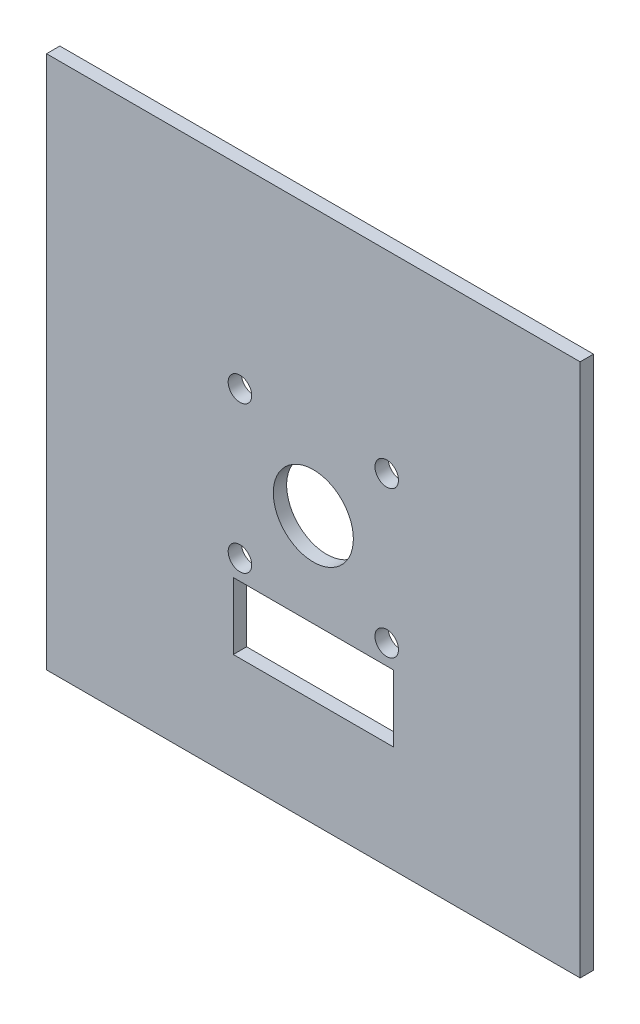
SolidWorks part; units mm, degrees
ref_plane "Front Plane" through (0, 0, 0) normal (0, 0, 1) x (1, 0, 0)
ref_plane "Top Plane" through (0, 0, 0) normal (0, 1, 0) x (1, 0, 0)
ref_plane "Right Plane" through (0, 0, 0) normal (1, 0, 0) x (0, 0, -1)
sketch "Sketch1" plane through (0, 0, 0) normal (0, 0, 1) x (1, 0, 0)
  line L0 (-259.5239, 0) -> (259.5239, 0) construction
  line L1 (0, -214.3934) -> (0, 214.3934) construction
  line L3 (-127, -127) -> (127, -127)
  line L4 (-127, -127) -> (-127, 127)
  line L5 (-127, 127) -> (127, 127)
  line L6 (127, -127) -> (127, 127)
  line L7 (-127, -127) -> (127, 127) construction
  line L8 (-127, 127) -> (127, -127) construction
  line L9 (-38.1, -76.2) -> (38.1, -76.2)
  line L10 (-38.1, -76.2) -> (-38.1, -44.45)
  line L11 (-38.1, -44.45) -> (38.1, -44.45)
  line L12 (38.1, -76.2) -> (38.1, -44.45)
  line L13 (-38.1, -76.2) -> (38.1, -44.45) construction
  line L14 (-38.1, -44.45) -> (38.1, -76.2) construction
  line L19 (-47.625, -47.625) -> (47.625, 47.625) construction
  line L20 (-47.625, 47.625) -> (47.625, -47.625) construction
  circle A0 centre (0, 0) radius 19.05
  circle A1 centre (-34.925, 34.925) radius 5.6031
  circle A2 centre (34.925, 34.925) radius 5.6031
  circle A3 centre (34.925, -34.925) radius 5.6031
  circle A4 centre (-34.925, -34.925) radius 5.6031
  point P0 (0, 0)
  point P4 (0, 0)
  point P8 (0, 0)
  point P15 (0, -60.325)
  point P26 (0, 0)
  dimension "D3" = 38.1
  dimension "D1" = 254
  dimension "D2" = 254
  dimension "D4" = 50.8
  dimension "D5" = 76.2
  dimension "D6" = 31.75
  dimension "D7" = 95.25
  dimension "D8" = 95.25
  dimension "D9" = 34.925
  dimension "D10" = 34.925
extrude "Boss-Extrude1" add sketch "Sketch1" along normal mid plane 6.35 contours L3 L6 L5 L4 A0 A1 A2 L10 A4 L11 A3 L12 L9
